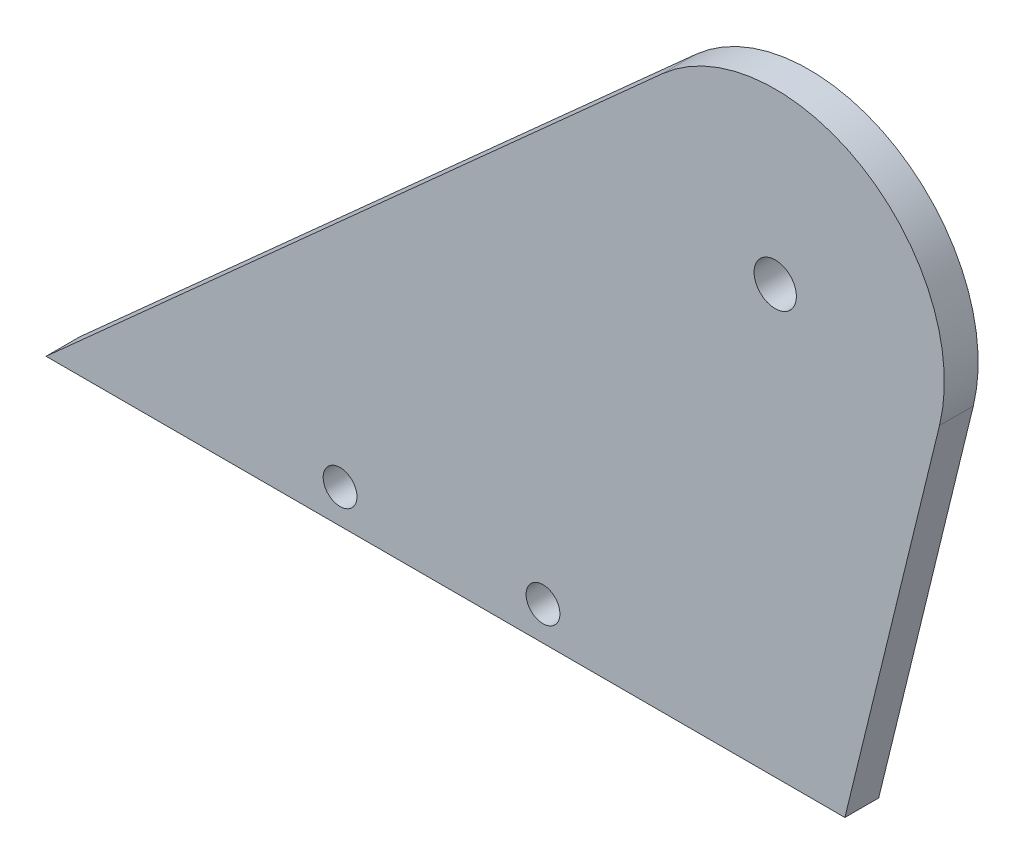
SolidWorks part; units mm, degrees
material "自訂玻璃纖維"
ref_plane "前基準面" through (0, 0, 0) normal (0, 0, 1) x (1, 0, 0)
ref_plane "上基準面" through (0, 0, 0) normal (0, 1, 0) x (1, 0, 0)
ref_plane "右基準面" through (0, 0, 0) normal (1, 0, 0) x (0, 0, -1)
sketch "草圖1" plane through (0, 0, 0) normal (0, 0, 1) x (1, 0, 0)
  line L0 (-41.0787, -25.2469) -> (3.125, -25.2469)
  line L1 (-43.1207, -25.2469) -> (-6.6774, 7.4439)
  line L2 (4.1185, -25.2469) -> (9.7136, -2.3763)
  line L4 (-43.1207, -25.2469) -> (-41.0787, -25.2469)
  line L6 (4.1185, -25.2469) -> (3.125, -25.2469)
  arc A0 (9.7136, -2.3763) -> (-6.6774, 7.4439) centre (0, 0) ccw
  circle A1 centre (0, 0) radius 1.25
  circle A8 centre (-25.7326, -23.2469) radius 1
  circle A9 centre (-13.7326, -23.2469) radius 1
  point P4 (3.9807, -25.2469)
  point P17 (0, 0)
  dimension "D1" = 20
  dimension "D2" = 2.5
  dimension "D7" = 12
extrude "填料-伸長1" add sketch "草圖1" along normal blind 2
